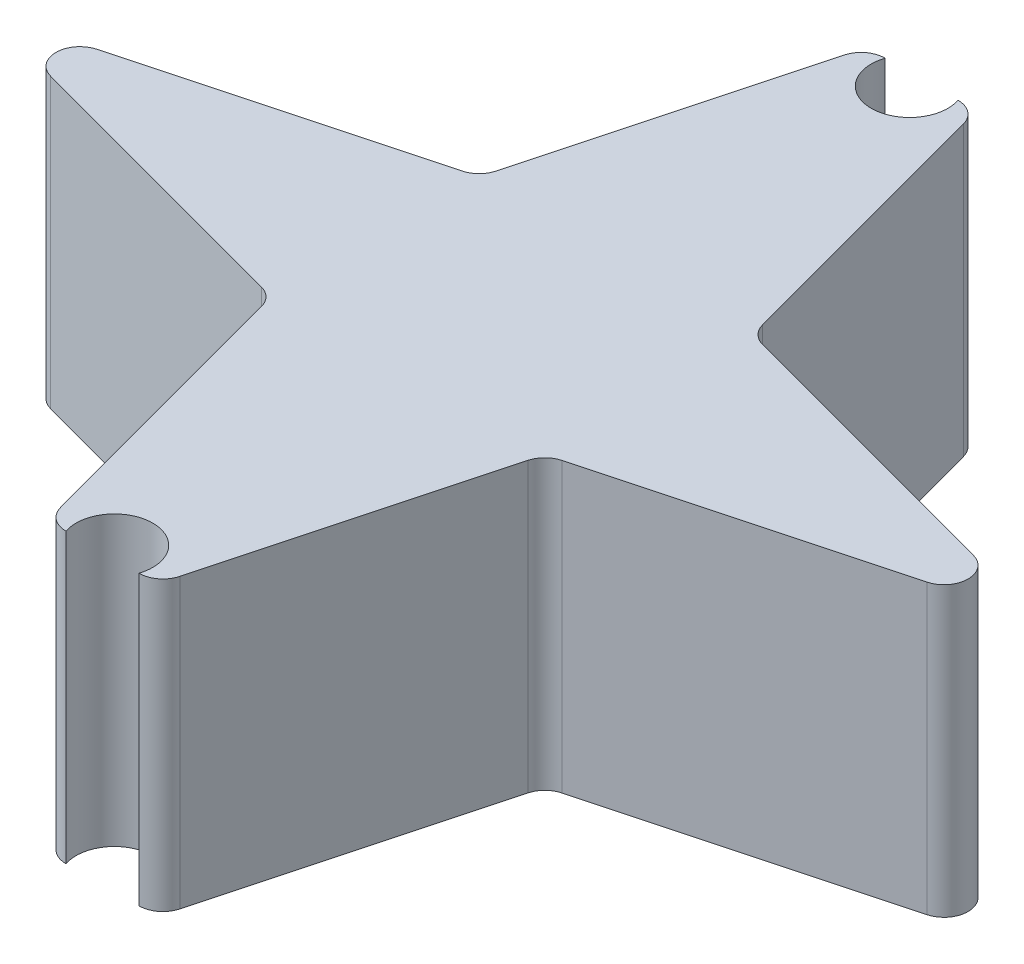
SolidWorks part; units mm, degrees
material "ABS"
ref_plane "Front" through (0, 0, 0) normal (0, 0, 1) x (1, 0, 0)
ref_plane "Top" through (0, 0, 0) normal (0, 1, 0) x (1, 0, 0)
ref_plane "Right" through (0, 0, 0) normal (1, 0, 0) x (0, 0, -1)
sketch "Esquisse1" plane through (0, 0, 0) normal (0, 1, 0) x (1, 0, 0)
  line L0 (0, 15.9138) -> (15.8981, -0.7069) construction
  line L1 (15.8981, -0.7069) -> (0, -15.9138) construction
  line L2 (0, 15.9138) -> (0, -15.9138) construction
  line L3 (2.4858, 16.3226) -> (5.5494, 4.889)
  line L4 (6.2565, 4.1819) -> (18.2588, 0.9659)
  line L5 (0, 0) -> (18, 0) construction
  line L6 (6.2565, -4.1819) -> (18.2588, -0.9659)
  line L7 (2.4858, -16.3226) -> (5.5494, -4.889)
  line L8 (-2.4858, 16.3226) -> (-5.5494, 4.889)
  line L9 (-6.2565, 4.1819) -> (-18.2588, 0.9659)
  line L10 (-6.2565, -4.1819) -> (-18.2588, -0.9659)
  line L11 (-2.4858, -16.3226) -> (-5.5494, -4.889)
  circle A0 centre (0, 15.9138) radius 2.25 construction
  arc A1 (-1.5199, 17.0638) -> (1.5199, 17.0638) centre (0, 16.5638) ccw
  arc A2 (18.2588, 0.9659) -> (18.2588, -0.9659) centre (18, 0) cw
  arc A3 (5.5494, 4.889) -> (6.2565, 4.1819) centre (6.5153, 5.1479) ccw
  arc A4 (2.4858, 16.3226) -> (1.5199, 17.0638) centre (1.5199, 16.0638) ccw
  arc A5 (5.5494, -4.889) -> (6.2565, -4.1819) centre (6.5153, -5.1479) cw
  arc A6 (2.4858, -16.3226) -> (1.5199, -17.0638) centre (1.5199, -16.0638) cw
  arc A7 (-1.5199, -17.0638) -> (1.5199, -17.0638) centre (0, -16.5638) cw
  arc A8 (-2.4858, 16.3226) -> (-1.5199, 17.0638) centre (-1.5199, 16.0638) cw
  arc A9 (-5.5494, 4.889) -> (-6.2565, 4.1819) centre (-6.5153, 5.1479) cw
  arc A10 (-18.2588, 0.9659) -> (-18.2588, -0.9659) centre (-18, 0) ccw
  arc A11 (-5.5494, -4.889) -> (-6.2565, -4.1819) centre (-6.5153, -5.1479) ccw
  arc A12 (-2.4858, -16.3226) -> (-1.5199, -17.0638) centre (-1.5199, -16.0638) ccw
  dimension "D1" = 4.5
  dimension "D4" = 3.2
  dimension "D5" = 1
  dimension "D6" = 0.5
  dimension "D9" = 36
  dimension "D2" = 23
  dimension "D3" = 22
  dimension "D7" = 15
  dimension "D8" = 15
extrude "Boss.-Extru.1" add sketch "Esquisse1" along normal blind 12
